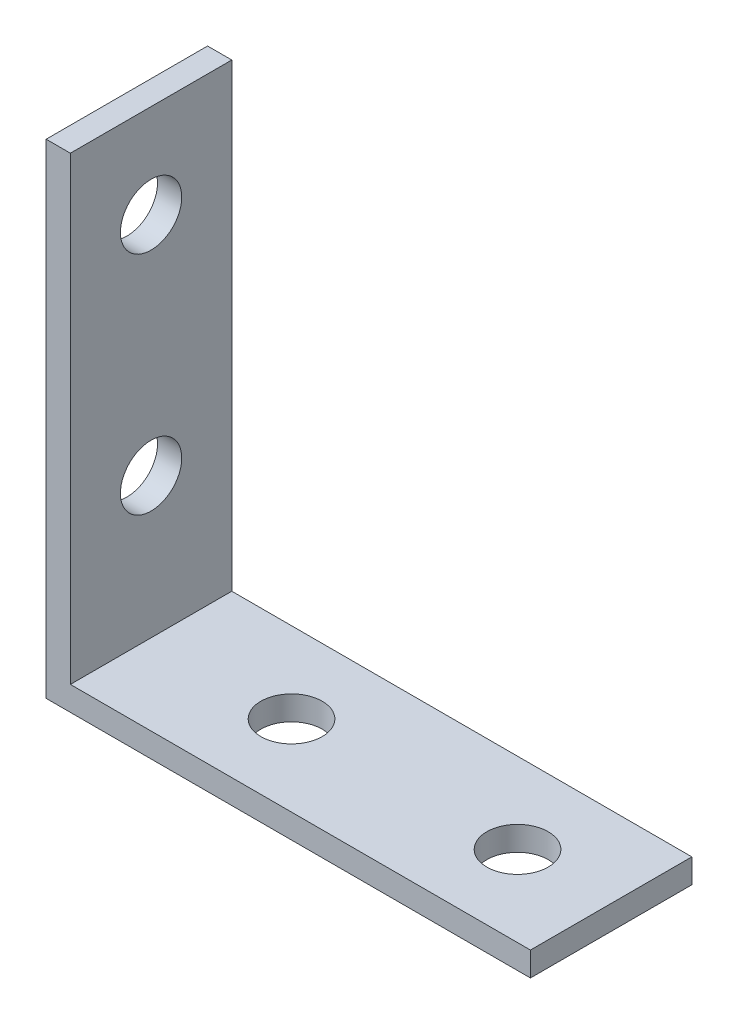
SolidWorks part; units mm, degrees
ref_plane "Front Plane" through (0, 0, 0) normal (0, 0, 1) x (1, 0, 0)
ref_plane "Top Plane" through (0, 0, 0) normal (0, 1, 0) x (1, 0, 0)
ref_plane "Right Plane" through (0, 0, 0) normal (1, 0, 0) x (0, 0, -1)
sketch "Sketch1" plane through (0, 0, 0) normal (0, 0, 1) x (1, 0, 0)
  line L0 (0, 0) -> (0, 38.1)
  line L1 (0, 38.1) -> (1.905, 38.1)
  line L2 (1.905, 38.1) -> (1.905, 1.905)
  line L3 (1.905, 1.905) -> (38.1, 1.905)
  line L4 (38.1, 1.905) -> (38.1, 0)
  line L5 (38.1, 0) -> (0, 0)
  dimension "D1" = 38.1
  dimension "D2" = 1.905
extrude "Boss-Extrude1" add sketch "Sketch1" along normal blind 12.7
sketch "Sketch2" plane through (1.905, 0, 0) normal (1, 0, 0) x (0, 0, -1)
  line L0 (-6.35, 30.734) -> (-6.35, 38.1) construction
  line L1 (-12.7, 38.1) -> (0, 38.1) construction
  line L2 (-6.35, 38.1) -> (-6.35, 12.954) construction
  circle A0 centre (-6.35, 30.734) radius 2.413
  circle A1 centre (-6.35, 12.954) radius 2.413
  dimension "D1" = 4.826
  dimension "D2" = 7.366
  dimension "D3" = 25.146
extrude "Cut-Extrude1" cut sketch "Sketch2" against normal through all
ref_plane "Plane1" through (0, 0, 0) normal (-0.7071, 0.7071, 0) x (0.7071, 0.7071, 0)
mirror "Mirror1" about plane through (0, 0, 0) normal (-0.7071, 0.7071, 0) of "Cut-Extrude1"
